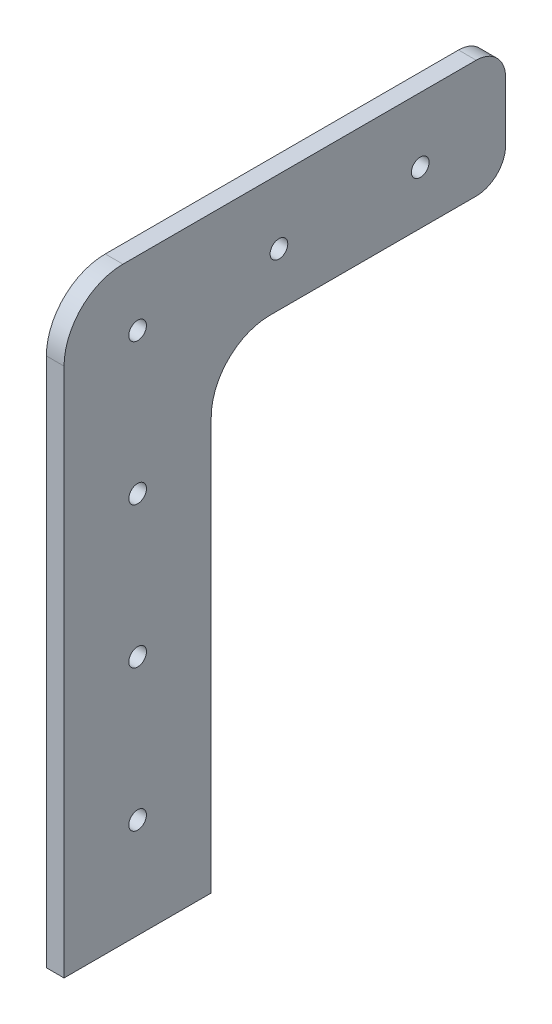
SolidWorks part; units mm, degrees
ref_plane "Alzado" through (0, 0, 0) normal (0, 0, 1) x (1, 0, 0)
ref_plane "Planta" through (0, 0, 0) normal (0, 1, 0) x (1, 0, 0)
ref_plane "Vista lateral" through (0, 0, 0) normal (1, 0, 0) x (0, 0, -1)
sketch "Croquis1" plane through (0, 0, 0) normal (1, 0, 0) x (0, 0, -1)
  line L1 (0, 0) -> (75, 0)
  line L2 (0, 0) -> (0, -100)
  line L3 (0, -100) -> (75, -100)
  line L4 (75, 0) -> (75, -100)
  dimension "D1" = 100
  dimension "D2" = 75
extrude "Saliente-Extruir1" add sketch "Croquis1" along normal blind 3
sketch "Croquis2" plane through (3, 0, 0) normal (1, 0, 0) x (0, 0, -1)
  line L1 (25, -20) -> (75, -20)
  line L2 (25, -20) -> (25, -100)
  line L3 (25, -100) -> (75, -100)
  line L4 (75, -20) -> (75, -100)
  dimension "D1" = 80
  dimension "D2" = 50
extrude "Cortar-Extruir1" cut sketch "Croquis2" against normal blind 3
fillet "Redondeo1" radius 10 2 edges at (1.5, -20, -25) (1.5, 0, 0)
fillet "Redondeo3" radius 5 2 edges at (1.5, 0, -75) (1.5, -20, -75)
sketch "Croquis3" plane through (3, 0, 0) normal (1, 0, 0) x (0, 0, -1)
  line L0 (0, -10) -> (0, -100) construction
  line L2 (0, -100) -> (25, -100) construction
  line L4 (70, -20) -> (35, -20) construction
  circle A0 centre (12.5, -11) radius 1.5
  circle A1 centre (12.5, -59) radius 1.5
  circle A2 centre (12.5, -83) radius 1.5
  circle A4 centre (12.5, -35) radius 1.5
  circle A5 centre (36.5, -11) radius 1.5
  circle A6 centre (60.5, -11) radius 1.5
  dimension "D1" = 3
  dimension "D2" = 3
  dimension "D3" = 3
  dimension "D4" = 3
  dimension "D5" = 3
  dimension "D6" = 12.5
  dimension "D7" = 12.5
  dimension "D8" = 12.5
  dimension "D9" = 12.5
  dimension "D10" = 17
  dimension "D11" = 24
  dimension "D12" = 24
  dimension "D13" = 24
  dimension "D14" = 3
  dimension "D15" = 24
  dimension "D16" = 24
  dimension "D17" = 9
  dimension "D18" = 9
extrude "Cortar-Extruir2" cut sketch "Croquis3" against normal blind 3
